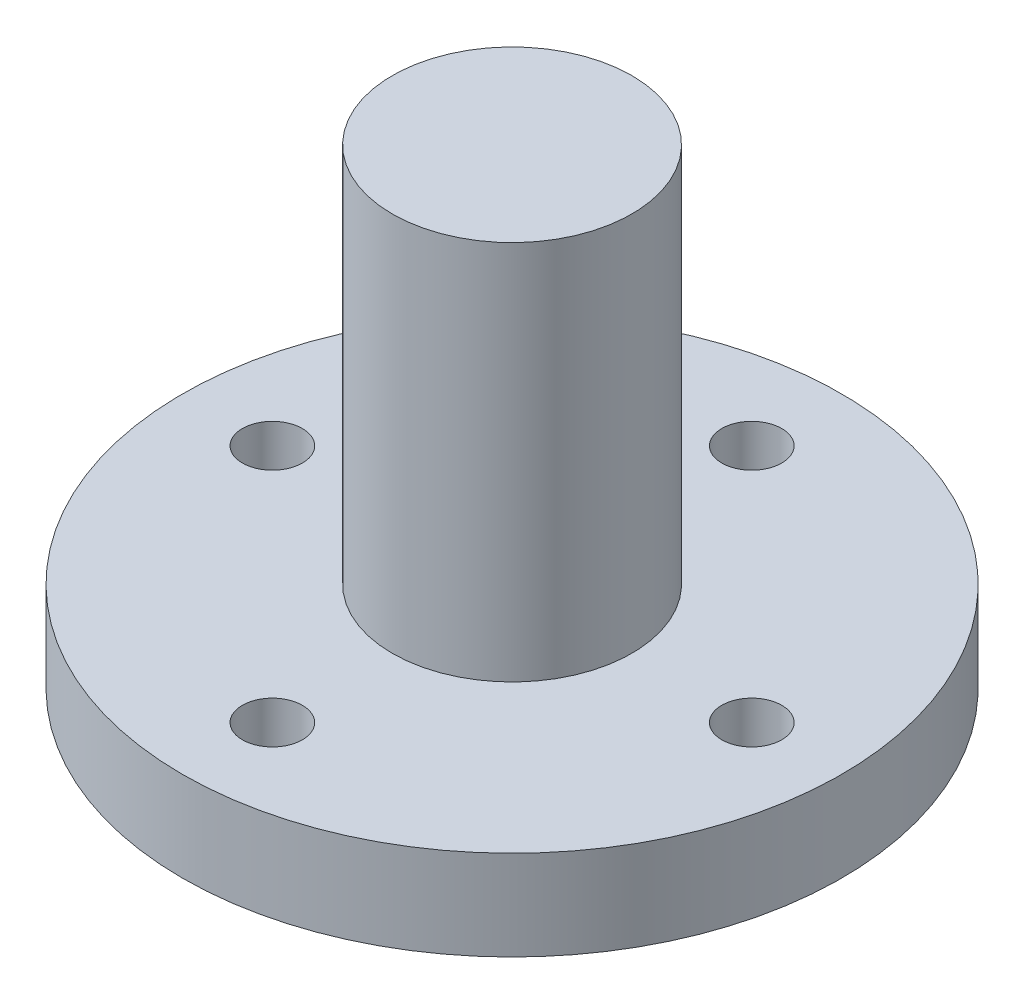
SolidWorks part; units mm, degrees
ref_plane "Front Plane" through (0, 0, 0) normal (0, 0, 1) x (1, 0, 0)
ref_plane "Top Plane" through (0, 0, 0) normal (0, 1, 0) x (1, 0, 0)
ref_plane "Right Plane" through (0, 0, 0) normal (1, 0, 0) x (0, 0, -1)
sketch "Sketch1" plane through (0, 0, 0) normal (0, 1, 0) x (1, 0, 0)
  line L0 (0, 0) -> (0, 8) construction
  circle A0 centre (0, 0) radius 11
  circle A1 centre (0, 8) radius 1
  circle A2 centre (8, 0) radius 1
  circle A3 centre (0, -8) radius 1
  circle A4 centre (-8, 0) radius 1
  dimension "D1" = 22
  dimension "D2" = 2
  dimension "D5" = 8
  dimension "D4" = 4
extrude "Boss-Extrude1" add sketch "Sketch1" along normal blind 3
sketch "Sketch2" plane through (0, 3, 0) normal (0, 1, 0) x (1, 0, 0)
  circle A1 centre (0, 0) radius 4
  dimension "D1" = 8
extrude "Boss-Extrude2" add sketch "Sketch2" along normal blind 12.7
